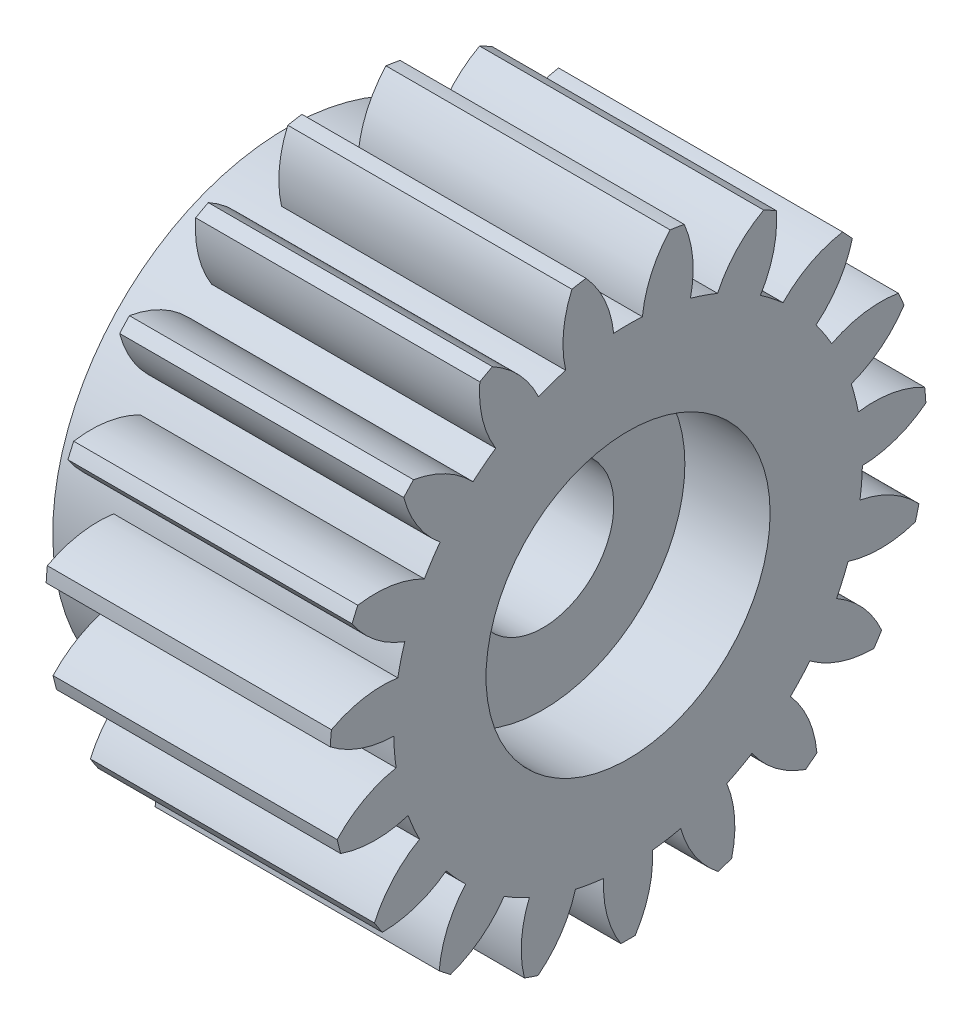
SolidWorks part; units mm, degrees
ref_plane "Plane1" through (0, 0, 0) normal (0, 0, 1) x (1, 0, 0)
ref_plane "Plane2" through (0, 0, 0) normal (0, 1, 0) x (1, 0, 0)
ref_plane "Plane3" through (0, 0, 0) normal (1, 0, 0) x (0, 0, -1)
other "Configuration Table"
sketch "HoldingSke" plane through (0, 0, 0) normal (0, 1, 0) x (1, 0, 0)
  line L0 (0, 0) -> (0.9455, -0.3256)
  line L1 (-15, 0) -> (100, 0) construction
  line L2 (0, 0) -> (-2.1039, 2.3779)
  line L3 (0, 0) -> (-11.863, 4.5341)
  line L4 (0, 0) -> (8.1655, 2.8116)
  line L5 (0, 0) -> (-46.8476, -17.4728)
  line L6 (0, 0) -> (-7.4607, -5.0337)
  line L7 (-2.1039, 2.3779) -> (8.6586, 51.2059)
  line L8 (-76.2, 54.61) -> (-75.3, 54.61)
  line L9 (-71.009, 38.7566) -> (-53.1078, 45.2721)
  line L10 (-76.2, 71.12) -> (104.1128, 71.12)
  line L11 (0, 0) -> (-9, 0)
  line L12 (-76.2, 101.6) -> (-76.162, 101.6)
  line L13 (24.9733, 27.94) -> (52.9518, 28.4284)
  line L14 (24.9733, 27.94) -> (24.9743, 27.94)
  line L15 (24.9733, 27.94) -> (100.4006, 29.5858)
  line L16 (-63.627, -1) -> (-12.827, -1)
  circle A0 centre (0, 0) radius 2.5
  circle A1 centre (0, 0) radius 8.249
  circle A2 centre (0, 0) radius 37.5
  circle A3 centre (0, 0) radius 2.5
  dimension "MHD" = 16.498
  dimension "Hub_dia" = 75
  dimension "Bore" = 5
  dimension "MBD" = 5
  dimension "Num_teeth" = 19
  dimension "Pitch" = 1
  dimension "Overall_len" = 50
  dimension "Show_teeth" = 19
  dimension "Thickness" = 9
  dimension "OAL" = 50.0001
  dimension "T_dim" = 0.9
  dimension "Ap" = 20
  dimension "H" = 19.05
  dimension "Pitch_radius" = 180.3128
  dimension "Width" = 9
  dimension "Backlash" = 0.038
  dimension "Addendum_fac" = 1
  dimension "Dedendum_fac" = 1.25
  dimension "Clearance_fac" = 0.25
  dimension "Dedendum_add" = 0.001
  dimension "Module" = 1
sketch "BasProSke" plane through (0, 0, 0) normal (0, 1, 0) x (1, 0, 0)
  line L0 (-10, 0) -> (60, 0) construction
  line L1 (0, 0) -> (0, 10.5)
  line L2 (0, 0) -> (12, 0)
  line L3 (12, 0) -> (12, 10.5)
  line L4 (12, 10.5) -> (0, 10.5)
  dimension "Thickness" = 12
  dimension "Diameter" = 21
revolve "Base-Revolve" add sketch "BasProSke" angle 360 about L0
sketch "TooCutSke" plane through (0, 0, 0) normal (1, 0, 0) x (0, 0, -1)
  line L1 (0, 0) -> (0, 107) construction
  line L2 (0, 0) -> (-0.851, 9.4618) construction
  line L3 (0, 0) -> (-3.1184, 18.6873) construction
  line L4 (-0.851, 9.4618) -> (-1.5592, 9.3436) construction
  arc A0 (0.505, 8.2335) -> (-0.505, 8.2335) centre (0, 0) ccw
  arc A1 (1.4994, 10.4181) -> (-1.4994, 10.4181) centre (0, 0) ccw
  circle A2 centre (0, 0) radius 9.5 construction
  circle A3 centre (0, 0) radius 8.9271 construction
  arc A4 (-0.505, 8.2335) -> (-1.4994, 10.4181) centre (-4.2838, 7.8321) ccw
  arc A5 (1.4994, 10.4181) -> (0.505, 8.2335) centre (4.2838, 7.8321) ccw
  dimension "Root_dia" = 16.498
  dimension "Overcut_dia" = 21.0508
  dimension "Pitch_dia" = 19
  dimension "Base_dia" = 17.8542
  dimension "Flank_rad" = 3.8
  dimension "Half_ang" = 9.474
  dimension "Half_CT" = 0.718
extrude "ToothCut" cut sketch "TooCutSke" along normal through all
fillet "Breaks" [suppressed] radius 0.02
fillet "RootFillets" [suppressed] radius 0.251
pattern_circular "TeethCuts" count 19 over 360 about axis through (0, 0, 0) along (1, 0, 0) of "ToothCut", "RootFillets", "Breaks"
sketch "HubNeaOneSke" plane through (0, 0, 0) normal (-1, 0, 0) x (0, 0, 1)
  circle A0 centre (0, 0) radius 8.249
  dimension "Diameter" = 16.498
extrude "HubNearOne" [suppressed] add sketch "HubNeaOneSke" along normal blind 38.0001
sketch "HubNeaBotSke" plane through (0, 0, 0) normal (-1, 0, 0) x (0, 0, 1)
  circle A0 centre (0, 0) radius 8.249
  dimension "Diameter" = 16.498
extrude "HubNearBoth" [suppressed] add sketch "HubNeaBotSke" along normal blind 19
ref_plane "FarPln" through (12, 0, 0) normal (1, 0, 0) x (0, 0, -1)
sketch "HubFarSke" plane through (12, 0, 0) normal (1, 0, 0) x (0, 0, -1)
  circle A0 centre (0, 0) radius 8.249
  dimension "Diameter" = 16.498
extrude "HubFar" [suppressed] add sketch "HubFarSke" along normal blind 19
sketch "BorSke" plane through (0, 0, 0) normal (1, 0, 0) x (0, 0, -1)
  circle A0 centre (0, 0) radius 2.5
  dimension "Diameter" = 5
extrude "Bore" cut sketch "BorSke" along normal mid plane 100.0001
sketch "KeySke" plane through (0, 0, 0) normal (1, 0, 0) x (0, 0, -1)
  line L0 (-1, 0) -> (-1, 3.4)
  line L1 (-1, 3.4) -> (1, 3.4)
  line L2 (1, 3.4) -> (1, 0)
  line L3 (0, 0) -> (0, 34) construction
  line L4 (-1, 0) -> (1, 0)
  dimension "Offset" = 3.4
  dimension "Width" = 2
extrude "Keyway" [suppressed] cut sketch "KeySke" along normal mid plane 100.0001
pattern_circular "Keyway2" [suppressed] count 2 every 90 about axis through (-10, 0, 0) along (1, 0, 0)
sketch "Sketch1" plane through (12, 0, 0) normal (1, 0, 0) x (0, 0, -1)
  circle A0 centre (0, 0) radius 5
  dimension "D1" = 10
extrude "Cut-Extrude1" cut sketch "Sketch1" against normal blind 3
sketch "Sketch2" plane through (9, 0, 0) normal (1, 0, 0) x (0, 0, -1)
  line L0 (-2.0854, 1.3788) -> (-2.0854, -1.3788)
  circle A0 centre (0, 0) radius 2.5
  circle M1 centre (0, 0) radius 2.5
extrude "Boss-Extrude1" add sketch "Sketch2" against normal up to surface (9 mm away) contours L0 M1
sketch "Sketch3" plane through (0, 0, 0) normal (-1, 0, 0) x (0, 0, 1)
  circle A0 centre (0, 0) radius 8.249
  circle A1 centre (0, 0) radius 10.5
extrude "Cut-Extrude2" cut sketch "Sketch3" against normal blind 2
equation "' \"Module@HoldingSke\" = 6.35"
equation "' \"Num_teeth@HoldingSke\" = 12"
equation "' \"Ap@HoldingSke\" =  20"
equation "' \"Ap@HoldingSke\" = 20"
equation "' \"Width@HoldingSke\" = 0.5 * 25.4"
equation "' \"Hub_dia@HoldingSke\"= 1 * 25.4"
equation "' \"Hub_dia@HoldingSke\" = 1 * 25.4"
equation "' \"Overall_len@HoldingSke\" = 1.0 * 25.4"
equation "' \"Bore@HoldingSke\" = 0.75 * 25.4"
equation "' \"T_dim@HoldingSke\" = 0.1 * 25.4"
equation "' \"Width@KeySke\" = 0.25 * 25.4"
equation "' \"Show_teeth@HoldingSke\" = 13"
equation "' \"Backlash@HoldingSke\" = 0.009 * 25.4"
equation "' \"Addendum_fac@HoldingSke\" = 1.0"
equation "' \"Dedendum_fac@HoldingSke\" = 1.25"
equation "' \"Dedendum_add@HoldingSke\" = 0.00005 * 25.4"
equation "' \"Clearance_fac@HoldingSke\" = 0.25"
equation "\"Pitch@HoldingSke\" = 1 / \"Module@HoldingSke\""
equation "\"Overcut_dia@TooCutSke\" = (\"Num_teeth@HoldingSke\" + 2 * \"Addendum_fac@HoldingSke\") / \"Pitch@HoldingSke\" + 0.002 * 25.4"
equation "\"Pitch_dia@TooCutSke\" = \"Num_teeth@HoldingSke\" / \"Pitch@HoldingSke\""
equation "\"Base_dia@TooCutSke\" = \"Num_teeth@HoldingSke\" / \"Pitch@HoldingSke\" * cos((\"Ap@HoldingSke\"  * 3.14159265 / 180))"
equation "\"Root_dia@TooCutSke\" = (\"Num_teeth@HoldingSke\" + 2) / \"Pitch@HoldingSke\" - 2 * (\"Addendum_fac@HoldingSke\" + \"Dedendum_fac@HoldingSke\") / \"Pitch@HoldingSke\" - \"Dedendum_add@HoldingSke\" * 2"
equation "\"Half_ang@TooCutSke\" = 180 / \"Num_teeth@HoldingSke\""
equation "\"Half_CT@TooCutSke\" = \"Num_teeth@HoldingSke\" / \"Pitch@HoldingSke\" * sin((3.14159265 / 2 / \"Num_teeth@HoldingSke\")) / 2 - 7 * \"Backlash@HoldingSke\" / 4"
equation "\"Flank_rad@TooCutSke\" = \"Num_teeth@HoldingSke\" / \"Pitch@HoldingSke\" / 5"
equation "\"Radius@RootFillets\" = \"Clearance_fac@HoldingSke\" / \"Pitch@HoldingSke\" + \"Dedendum_add@HoldingSke\""
equation "\"Break_rad@Breaks\" = 0.02 / \"Pitch@HoldingSke\""
equation "\"Thickness@HoldingSke\" = \"Width@HoldingSke\""
equation "\"OAL@HoldingSke\" = \"Thickness@HoldingSke\""
equation "\"MHD@HoldingSke\" = (\"Num_teeth@HoldingSke\" + 2) / \"Pitch@HoldingSke\" - 2 * (\"Addendum_fac@HoldingSke\" + \"Dedendum_fac@HoldingSke\")  / \"Pitch@HoldingSke\" - \"Dedendum_add@HoldingSke\" * 2"
equation "\"MBD@HoldingSke\" = (\"Num_teeth@HoldingSke\" + 2) / \"Pitch@HoldingSke\" - 2 * (\"Addendum_fac@HoldingSke\" + \"Dedendum_fac@HoldingSke\")  / \"Pitch@HoldingSke\" - \"Dedendum_add@HoldingSke\" * 2 - 0.002 * 25.4"
equation "\"MHD@HoldingSke\" = ((sgn( \"MHD@HoldingSke\" - \"Hub_dia@HoldingSke\" )-1)*( \"MHD@HoldingSke\" - \"Hub_dia@HoldingSke\" ))/-2+ \"Hub_dia@HoldingSke\""
equation "\"MBD@HoldingSke\" = ((sgn( \"MBD@HoldingSke\" - \"Bore@HoldingSke\" )-1)*( \"MBD@HoldingSke\" - \"Bore@HoldingSke\" ))/-2+ \"Bore@HoldingSke\""
equation "\"OAL@HoldingSke\" = ((sgn( \"OAL@HoldingSke\" - \"Overall_len@HoldingSke\" )+1)*( \"OAL@HoldingSke\" - \"Overall_len@HoldingSke\" ))/2 + \"Overall_len@HoldingSke\" + 0.000002 * 25.4"
equation "\"Num_teeth@TeethCuts\" = int( \"Show_teeth@HoldingSke\" ) + 1"
equation "\"Num_teeth@TeethCuts\" = ((sgn( \"Num_teeth@TeethCuts\" - \"Num_teeth@HoldingSke\" )-1)*( \"Num_teeth@TeethCuts\" - \"Num_teeth@HoldingSke\" ))/-2+ \"Num_teeth@HoldingSke\""
equation "\"Num_teeth@TeethCuts\" = ((sgn( \"Num_teeth@TeethCuts\" - 2.0)+1)*( \"Num_teeth@TeethCuts\" - 2.0))/2 +2.0"
equation "\"Angle@TeethCuts\" = 360.0 / \"Num_teeth@HoldingSke\""
equation "\"Diameter@BasProSke\" = (\"Num_teeth@HoldingSke\" + 2 * \"Addendum_fac@HoldingSke\") / \"Pitch@HoldingSke\""
equation "' \"Fillet_rad@BasProSke\" =  \"Thickness@HoldingSke\" * 0.05"
equation "' \"Fillet_rad@BasProSke\" = \"Thickness@HoldingSke\" * 0.05"
equation "\"MHD@HoldingSke\" = ((sgn( \"MHD@HoldingSke\" - \"Root_dia@TooCutSke\" )-1)*( \"MHD@HoldingSke\" - \"Root_dia@TooCutSke\" ))/-2+ \"Root_dia@TooCutSke\""
equation "\"Diameter@HubNeaOneSke\" = \"MHD@HoldingSke\""
equation "\"Length@HubNearOne\" = \"OAL@HoldingSke\" - \"Thickness@BasProSke\""
equation "\"Diameter@HubNeaBotSke\" = \"MHD@HoldingSke\""
equation "\"Length@HubNearBoth\" = ( \"OAL@HoldingSke\" - \"Thickness@BasProSke\" ) / 2.0"
equation "\"Thickness@FarPln\" = \"Thickness@BasProSke\""
equation "\"Diameter@HubFarSke\" = \"MHD@HoldingSke\""
equation "\"Length@HubFar\" = ( \"OAL@HoldingSke\" - \"Thickness@BasProSke\" ) / 2.0"
equation "\"Diameter@BorSke\" = \"MBD@HoldingSke\""
equation "\"D1@Bore\" = \"OAL@HoldingSke\" * 2.0"
equation "\"D1@Keyway\" = \"OAL@HoldingSke\" * 2.0"
equation "\"Offset@KeySke\" = \"T_dim@HoldingSke\" + \"MBD@HoldingSke\" / 2.0"
